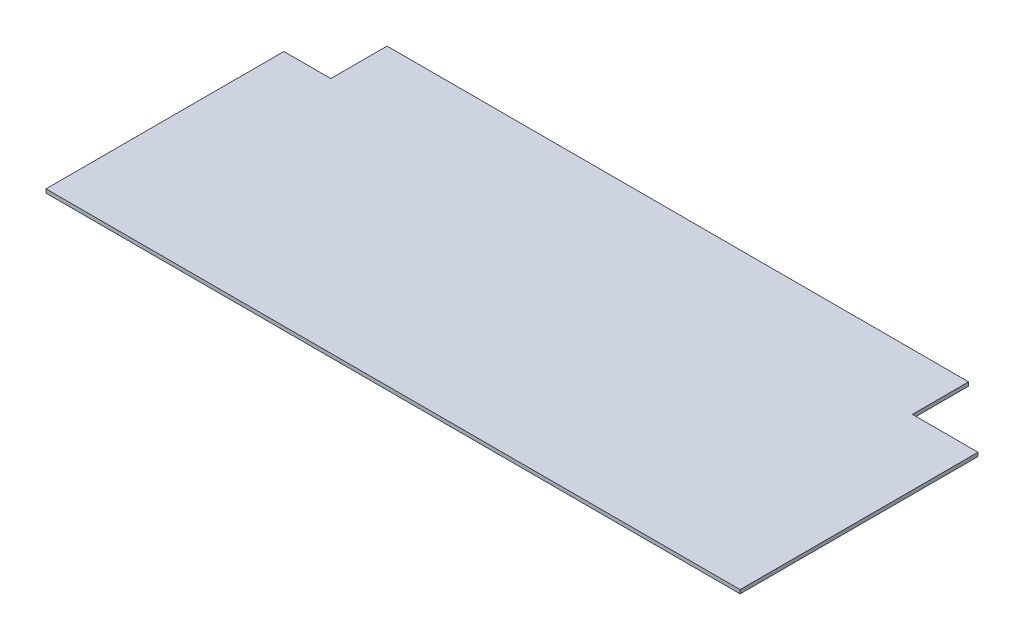
SolidWorks part; units mm, degrees
ref_plane "Front Plane" through (0, 0, 0) normal (0, 0, 1) x (1, 0, 0)
ref_plane "Top Plane" through (0, 0, 0) normal (0, 1, 0) x (1, 0, 0)
ref_plane "Right Plane" through (0, 0, 0) normal (1, 0, 0) x (0, 0, -1)
sketch "Sketch1" plane through (0, 0, 0) normal (0, 1, 0) x (1, 0, 0)
  line L0 (-130.625, 172.6078) -> (351.9808, 172.6078) construction
  line L1 (-124.2728, -32.8782) -> (345.6286, -32.8782)
  line L2 (-124.2728, -32.8782) -> (-124.2728, 166.2578)
  line L3 (-124.2728, 166.2578) -> (345.6286, 166.2578)
  line L4 (345.6286, -32.8782) -> (345.6286, 166.2578)
  line L13 (-124.2728, 166.2578) -> (-92.5228, 166.2578)
  line L14 (-124.2728, 166.2578) -> (-124.2728, 128.1578)
  line L15 (-124.2728, 128.1578) -> (-92.5228, 128.1578)
  line L16 (-92.5228, 166.2578) -> (-92.5228, 128.1578)
  line L17 (345.6286, 166.2578) -> (301.1786, 166.2578)
  line L18 (345.6286, 166.2578) -> (345.6286, 128.1578)
  line L19 (345.6286, 128.1578) -> (301.1786, 128.1578)
  line L20 (301.1786, 166.2578) -> (301.1786, 128.1578)
  line L21 (351.9786, 172.6078) -> (351.9786, -36.9422) construction
  line L22 (351.9808, -39.2282) -> (-130.625, -39.2282) construction
  line L23 (-130.6228, -39.2282) -> (-130.6228, 172.6078) construction
  point P19 (-104.5226, 121.8078)
  dimension "D1" = 6.35
  dimension "D2" = 476.2514
  dimension "D3" = 6.35
  dimension "D4" = 6.35
  dimension "D5" = 6.35
  dimension "D6" = 38.1
  dimension "D7" = 31.75
  dimension "D8" = 44.45
extrude "Boss-Extrude1" add sketch "Sketch1" along normal blind 2.54 contours L1 L20 L19 L4 L3 L2 L15 L16
